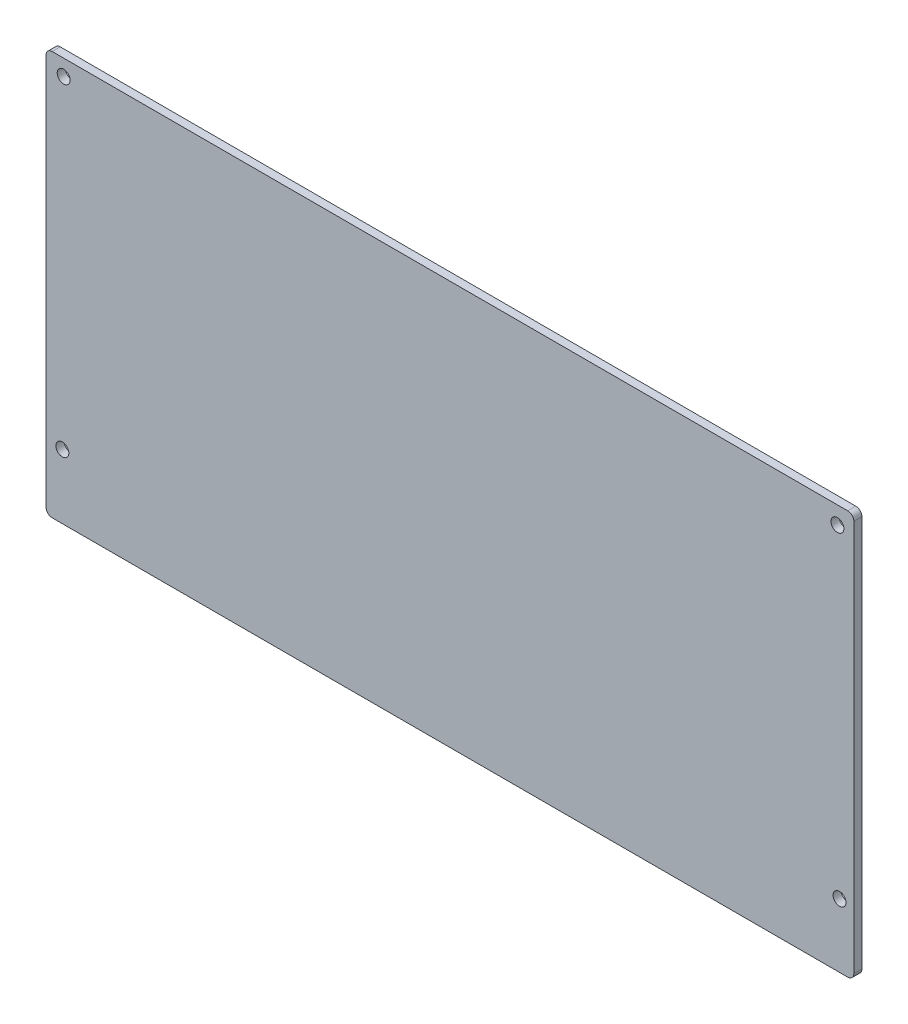
SolidWorks part; units mm, degrees
ref_plane "前视基准面" through (0, 0, 0) normal (0, 0, 1) x (1, 0, 0)
ref_plane "上视基准面" through (0, 0, 0) normal (0, 1, 0) x (1, 0, 0)
ref_plane "右视基准面" through (0, 0, 0) normal (1, 0, 0) x (0, 0, -1)
sketch "草图1" plane through (0, 0, 14.6001) normal (0, 0, 1) x (1, 0, 0)
  line L0 (240.6725, -244.8438) -> (44.6721, -244.8438) construction
  line L1 (42.6848, -144.8438) -> (242.6848, -144.8438)
  line L2 (42.6848, -144.8438) -> (42.6848, -244.8438)
  line L3 (42.6848, -244.8438) -> (242.6848, -244.8438)
  line L4 (242.6848, -144.8438) -> (242.6848, -244.8438)
  line L5 (42.6848, -242.8565) -> (42.6848, -146.8563) construction
  dimension "D1" = 200
  dimension "D2" = 100
  dimension "D3" = 0
  dimension "D4" = 0
extrude "凸台-拉伸1" add sketch "草图1" along normal blind 2
sketch "草图2" plane through (0, 0, 16.6001) normal (0, 0, 1) x (1, 0, 0)
  circle A0 centre (47.0336, -148.8045) radius 1.6
  circle A1 centre (238.6242, -149.1693) radius 1.6
  circle A2 centre (46.7077, -228.9127) radius 1.6
  circle A3 centre (239.1469, -229.075) radius 1.6
  dimension "D1" = 3.2
  dimension "D2" = 3.2
  dimension "D3" = 3.2
  dimension "D4" = 3.2
extrude "切除-拉伸1" cut sketch "草图2" against normal blind 2
fillet "圆角1" radius 1.5 4 edges at (42.6848, -144.8438, 15.6001) (242.6848, -144.8438, 15.6001) (242.6848, -244.8438, 15.6001) (42.6848, -244.8438, 15.6001)
